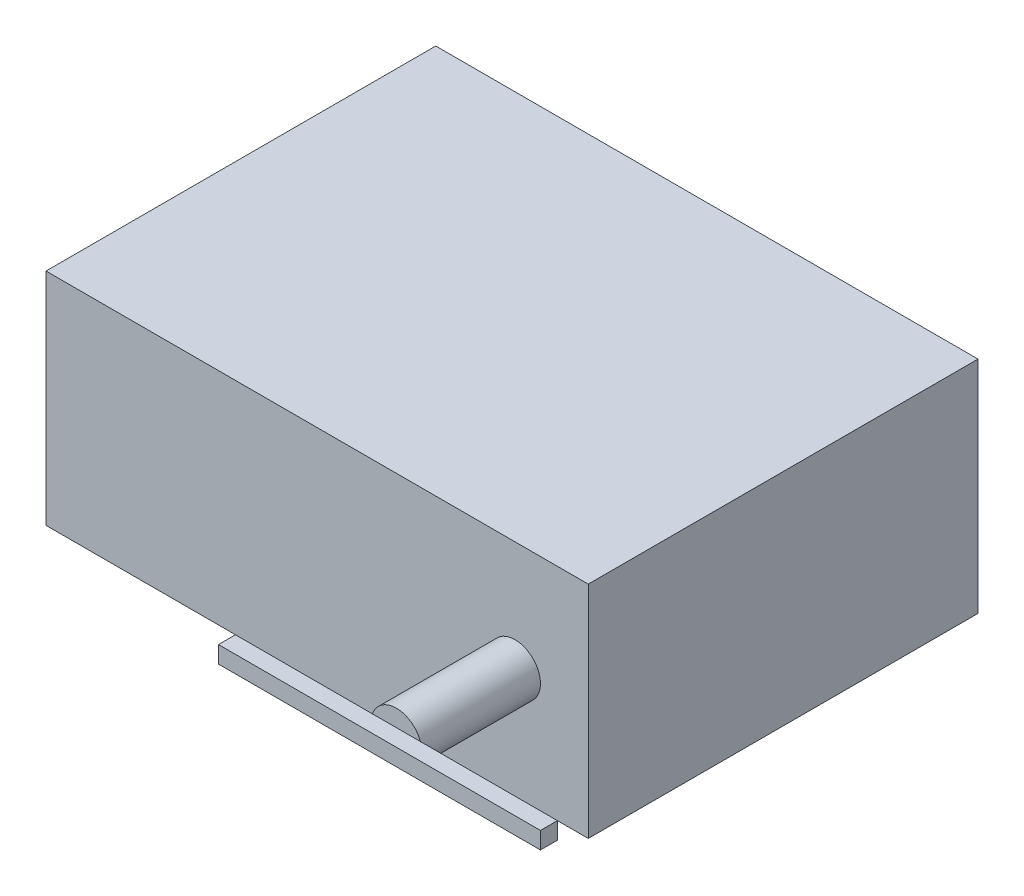
SolidWorks part; units mm, degrees
ref_plane "前视基准面" through (0, 0, 0) normal (0, 0, 1) x (1, 0, 0)
ref_plane "上视基准面" through (0, 0, 0) normal (0, 1, 0) x (1, 0, 0)
ref_plane "右视基准面" through (0, 0, 0) normal (1, 0, 0) x (0, 0, -1)
sketch "草图1" plane through (0, 0, 0) normal (0, 0, 1) x (1, 0, 0)
  line L0 (0, 0) -> (32, 0)
  line L1 (32, 0) -> (32, 13)
  line L2 (32, 13) -> (0, 13)
  line L3 (0, 13) -> (0, 0)
  dimension "D1" = 32
  dimension "D2" = 13
extrude "凸台-拉伸1" add sketch "草图1" along normal blind 23
sketch "草图2" plane through (0, 0, 23) normal (0, 0, 1) x (1, 0, 0)
  line L0 (32, 6.5) -> (27.6787, 6.5) construction
  line L1 (32, 0) -> (32, 13) construction
  circle A0 centre (27.6787, 6.5) radius 1.5
  dimension "D1" = 3
extrude "凸台-拉伸2" add sketch "草图2" along normal blind 7
sketch "草图3" plane through (0, 0, 30) normal (0, 0, 1) x (1, 0, 0)
  line L0 (27.6787, 6.5) -> (18.1787, 6.5) construction
  line L1 (27.6787, 7) -> (27.6787, 6)
  line L2 (27.6787, 6) -> (18.1787, 6)
  line L3 (18.1787, 6) -> (18.1787, 7)
  line L4 (27.6787, 7) -> (18.1787, 7)
  dimension "D1" = 0.5
  dimension "D2" = 9.5
extrude "凸台-拉伸3" add sketch "草图3" along normal blind 1
mirror "镜向1" about plane through (27.6787, 7, 31) normal (-1, 0, 0) of "凸台-拉伸3"
